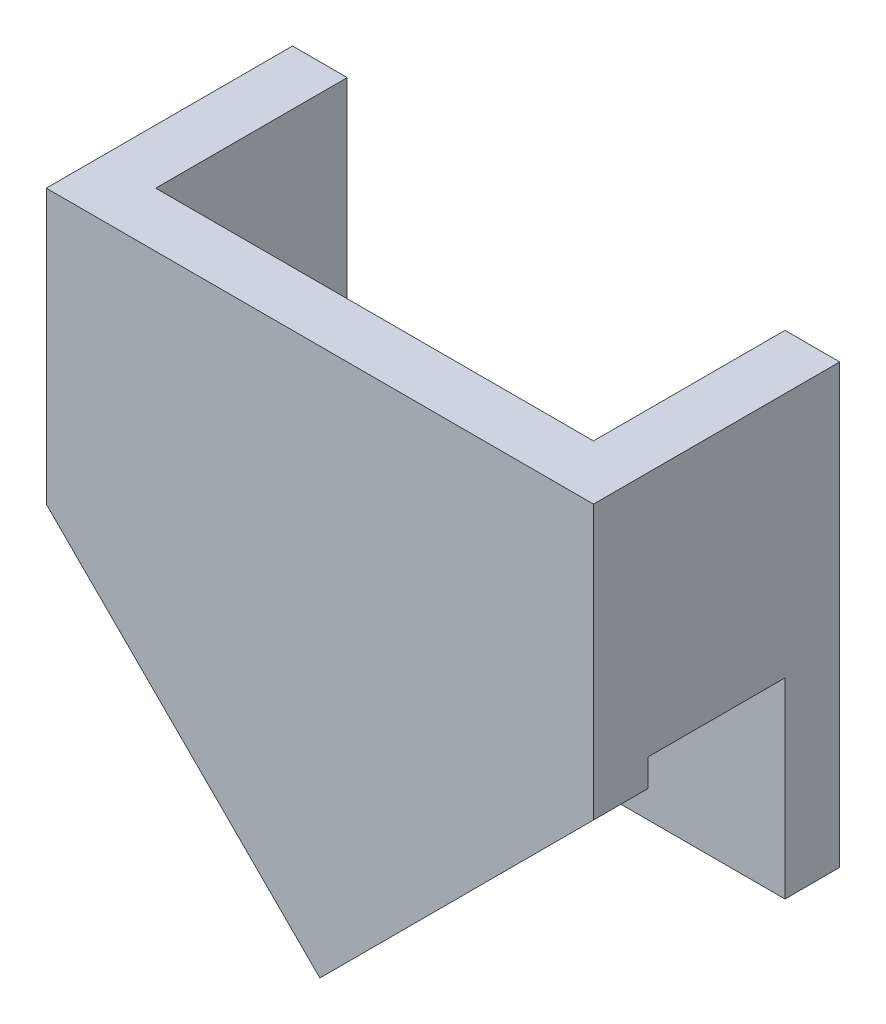
SolidWorks part; units mm, degrees
ref_plane "Front Plane" through (0, 0, 0) normal (0, 0, 1) x (1, 0, 0)
ref_plane "Top Plane" through (0, 0, 0) normal (0, 1, 0) x (1, 0, 0)
ref_plane "Right Plane" through (0, 0, 0) normal (1, 0, 0) x (0, 0, -1)
sketch "Sketch2" plane through (0, 0, 0) normal (0, 1, 0) x (1, 0, 0)
  line L0 (-40, 22.5) -> (-40, -12.5)
  line L1 (40, 22.5) -> (40, -12.5)
  line L2 (50, -22.5) -> (-50, -22.5)
  line L3 (50, -22.5) -> (50, 22.5)
  line L4 (50, 22.5) -> (40, 22.5)
  line L5 (-50, -22.5) -> (-50, 22.5)
  line L6 (50, -22.5) -> (-50, 22.5) construction
  line L7 (50, 22.5) -> (-50, -22.5) construction
  line L8 (40, -12.5) -> (-40, -12.5)
  line L9 (-40, 22.5) -> (-50, 22.5)
  point P1 (0, 0)
  dimension "D1" = 10
  dimension "10" = 10
  dimension "D2" = 10
  dimension "D3" = 100
  dimension "D4" = 45
extrude "Boss-Extrude1" add sketch "Sketch2" along normal blind 100
sketch "Sketch4" plane through (0, 0, 0) normal (1, 0, 0) x (0, 0, -1)
  line L0 (0, 100) -> (0, 55) construction
  line L1 (-22.5, 100) -> (22.5, 100) construction
  line L2 (0, 55) -> (-12.5, 55) construction
  line L3 (-12.5, 55) -> (12.5, 55) construction
  line L4 (-12.5, 55) -> (12.5, 55)
  line L5 (-12.5, 55) -> (-12.5, 0)
  line L6 (12.5, 55) -> (12.5, 0)
  line L7 (-22.5, 0) -> (22.5, 0) construction
  line L8 (12.5, 0) -> (-12.5, 0)
  dimension "D1" = 45
  dimension "D2" = 12.5
  dimension "D3" = 12.5
extrude "Cut-Extrude8" cut sketch "Sketch4" against normal blind 100 and the other way blind 100 contours L8 L5 L4 L6
sketch "Sketch5" plane through (0, 0, 22.5) normal (0, 0, 1) x (1, 0, 0)
  line L0 (-50, 50) -> (0, 0)
  line L1 (-50, 100) -> (-50, 0) construction
  line L8 (-50, 50) -> (-50, 0)
  line L9 (-50, 0) -> (0, 0)
extrude "Cut-Extrude9" cut sketch "Sketch5" against normal blind 10
sketch "Sketch6" plane through (0, 0, 22.5) normal (0, 0, 1) x (1, 0, 0)
  line L0 (0, 0) -> (50, 50)
  line L1 (50, 100) -> (50, 0) construction
  line L2 (50, 50) -> (50, 0)
  line L3 (50, 0) -> (0, 0)
extrude "Cut-Extrude10" cut sketch "Sketch6" against normal blind 10
sketch "Sketch7" plane through (0, 0, -22.5) normal (0, 0, -1) x (-1, 0, 0)
  line L0 (-40, 65) -> (40, 65)
  line L1 (-40, 100) -> (-40, 55) construction
  line L2 (40, 100) -> (40, 0) construction
  line L3 (40, 65) -> (40, 0)
  line L4 (40, 0) -> (-40, 0)
  line L5 (-40, 0) -> (-40, 65)
  dimension "D1" = 35
extrude "Boss-Extrude2" add sketch "Sketch7" against normal blind 10 separate body
sketch "Sketch8" plane through (0, 0, -22.5) normal (0, 0, -1) x (-1, 0, 0)
  line L1 (50, 20) -> (-50, 20)
  line L2 (50, 20) -> (50, 0)
  line L3 (50, 0) -> (-50, 0)
  line L4 (-50, 20) -> (-50, 0)
  line L5 (50, 20) -> (-50, 0) construction
  line L6 (50, 0) -> (-50, 20) construction
  point P0 (0, 10)
  dimension "D1" = 20
  dimension "D2" = 100
extrude "Cut-Extrude11" cut sketch "Sketch8" against normal blind 10
sketch "Sketch9" plane through (-40, 0, 0) normal (1, 0, 0) x (0, 0, -1)
  line L5 (-12.5, 65) -> (12.5, 65)
  line L6 (-22.5, 100) -> (22.5, 100) construction
  line L7 (-22.5, 100) -> (-22.5, 50) construction
  line L9 (-12.5, 65) -> (-12.5, 50)
  line L10 (-12.5, 50) -> (12.5, 50)
  line L11 (12.5, 55) -> (12.5, 20) construction
  line L12 (12.5, 65) -> (12.5, 50)
  dimension "D1" = 35
  dimension "D2" = 25
  dimension "D3" = 10
  dimension "D4" = 15
extrude "Boss-Extrude11" add sketch "Sketch9" along normal blind 90 and the other way blind 10
sketch "Sketch10" plane through (0, 0, 0) normal (0, 0, 1) x (1, 0, 0)
  line L0 (-50, 100) -> (50, 100) construction
  line L1 (50, 100) -> (50, 50) construction
  line L3 (50, 55) -> (46.1603, 55)
  line L5 (40, 65) -> (-40, 65)
  line L7 (28.8397, 55) -> (-28.8397, 55)
  line L8 (-46.1603, 55) -> (-50, 55)
  line L9 (-50, 100) -> (-40, 100)
  line L10 (-40, 100) -> (-40, 65)
  line L11 (50, 100) -> (40, 100)
  line L12 (40, 100) -> (40, 65)
  line L13 (-50, 100) -> (-50, 55)
  line L14 (50, 100) -> (50, 55)
  arc A2 (-46.1603, 55) -> (-28.8397, 55) centre (-37.5, 60) ccw
  arc A3 (28.8397, 55) -> (46.1603, 55) centre (37.5, 60) ccw
  point P8 (0, 60)
  dimension "D3" = 40
  dimension "D4" = 40
  dimension "D5" = 75
  dimension "D6" = 12.5
  dimension "D8" = 35
  dimension "D9" = 10
  dimension "D10" = 10
extrude "Cut-Extrude16" cut sketch "Sketch10" against normal blind 12.5 and the other way blind 12.5 flip side to cut
